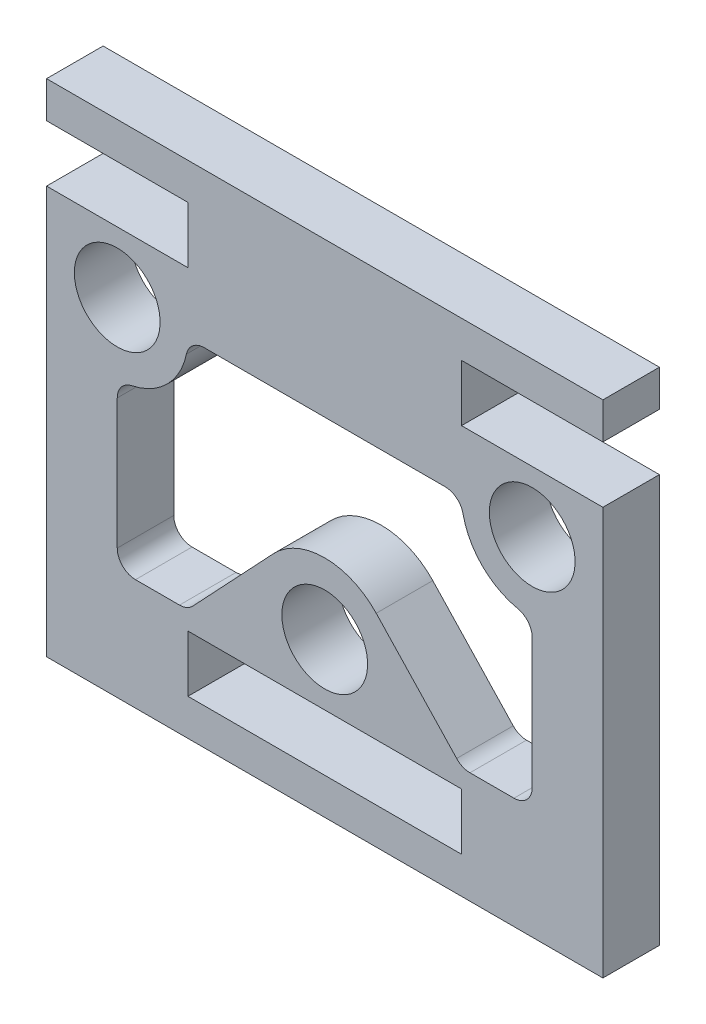
SolidWorks part; units mm, degrees
ref_plane "Front Plane" through (0, 0, 0) normal (0, 0, 1) x (1, 0, 0)
ref_plane "Top Plane" through (0, 0, 0) normal (0, 1, 0) x (1, 0, 0)
ref_plane "Right Plane" through (0, 0, 0) normal (1, 0, 0) x (0, 0, -1)
sketch "Sketch1" plane through (0, 0, 0) normal (0, 0, 1) x (1, 0, 0)
  line L0 (-25.7632, 28.4085) -> (-25.7632, 13.1585) construction
  line L1 (-41.0132, 34.5085) -> (-10.5132, 34.5085)
  line L2 (-41.0132, 34.5085) -> (-41.0132, 32.5085)
  line L3 (-18.2632, 32.5085) -> (-18.2632, 29.4085)
  line L4 (-10.5132, 34.5085) -> (-10.5132, 32.5085)
  line L5 (-37.1382, 21.2872) -> (-37.1382, 14.1585)
  line L6 (-22.9404, 18.1633) -> (-18.5296, 13.4734)
  line L7 (-10.5132, 29.4085) -> (-18.2632, 29.4085)
  line L8 (-41.0132, 29.4085) -> (-41.0132, 7.0585)
  line L9 (-10.5132, 29.4085) -> (-10.5132, 7.0585)
  line L10 (-10.5132, 32.5085) -> (-18.2632, 32.5085)
  line L11 (-41.0132, 32.5085) -> (-33.2632, 32.5085)
  line L12 (-14.3882, 21.2872) -> (-14.3882, 14.1585)
  line L13 (-33.2632, 12.1585) -> (-33.2632, 9.0585)
  line L14 (-33.2632, 12.1585) -> (-18.2632, 12.1585)
  line L15 (-10.5132, 20.7835) -> (-41.0132, 20.7835) construction
  line L16 (-18.2632, 12.1585) -> (-18.2632, 9.0585)
  line L17 (-33.2632, 9.0585) -> (-18.2632, 9.0585)
  line L18 (-36.1382, 13.1585) -> (-33.7251, 13.1585)
  line L19 (-41.0132, 7.0585) -> (-10.5132, 7.0585)
  line L20 (-32.3668, 26.0585) -> (-19.1595, 26.0585)
  line L21 (-41.0132, 29.4085) -> (-33.2632, 29.4085)
  line L22 (-33.2632, 32.5085) -> (-33.2632, 29.4085)
  line L23 (-32.9967, 13.4734) -> (-28.5859, 18.1633)
  line L24 (-17.8012, 13.1585) -> (-15.3882, 13.1585)
  circle A0 centre (-14.3882, 26.0585) radius 2.35
  circle A1 centre (-37.1382, 26.0585) radius 2.35
  circle A2 centre (-25.7632, 15.5085) radius 2.35
  arc A3 (-28.5859, 18.1633) -> (-22.9404, 18.1633) centre (-25.7632, 15.5085) cw
  arc A4 (-33.3456, 25.2636) -> (-36.3433, 22.2659) centre (-37.1382, 26.0585) cw
  arc A5 (-15.183, 22.2659) -> (-18.1808, 25.2636) centre (-14.3882, 26.0585) cw
  arc A6 (-37.1382, 21.2872) -> (-36.3433, 22.2659) centre (-36.1382, 21.2872) cw
  arc A7 (-32.3668, 26.0585) -> (-33.3456, 25.2636) centre (-32.3668, 25.0585) ccw
  arc A8 (-33.7251, 13.1585) -> (-32.9967, 13.4734) centre (-33.7251, 14.1585) ccw
  arc A9 (-18.1808, 25.2636) -> (-19.1595, 26.0585) centre (-19.1595, 25.0585) ccw
  arc A10 (-14.3882, 21.2872) -> (-15.183, 22.2659) centre (-15.3882, 21.2872) ccw
  arc A11 (-14.3882, 14.1585) -> (-15.3882, 13.1585) centre (-15.3882, 14.1585) cw
  arc A12 (-17.8012, 13.1585) -> (-18.5296, 13.4734) centre (-17.8012, 14.1585) cw
  arc A14 (-36.1382, 13.1585) -> (-37.1382, 14.1585) centre (-36.1382, 14.1585) cw
  point P38 (-33.2632, 26.0585)
  point P47 (-14.3882, 13.1585)
  point P49 (-33.2928, 13.1585)
  point P50 (-22.6821, 13.1585)
  point P53 (-28.8442, 13.1585)
  point P56 (-37.1382, 13.1585)
  point P59 (-18.2335, 13.1585)
  dimension "D6" = 1
  dimension "D7" = 4.7
  dimension "D8" = 4.7
  dimension "D5" = 1
  dimension "D1" = 30.5
  dimension "D2" = 3.1
  dimension "D3" = 15.25
  dimension "D4" = 2
extrude "Extrude1" add sketch "Sketch1" along normal blind 3.1
